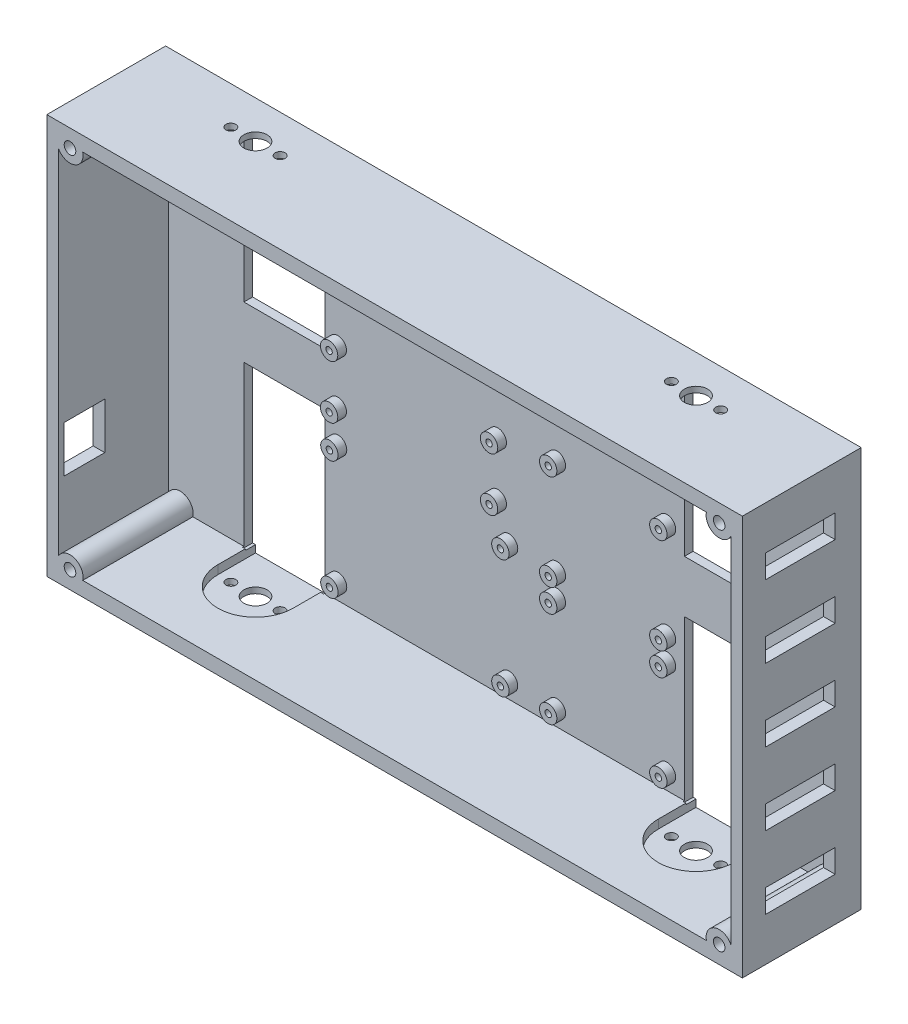
SolidWorks part; units mm, degrees
ref_plane "Front Plane" through (0, 0, 0) normal (0, 0, 1) x (1, 0, 0)
ref_plane "Top Plane" through (0, 0, 0) normal (0, 1, 0) x (1, 0, 0)
ref_plane "Right Plane" through (0, 0, 0) normal (1, 0, 0) x (0, 0, -1)
ref_plane "P_Front_57" through (0, 0, 57) normal (0, 0, 1) x (1, 0, 0)
sketch "Sketch1" plane through (0, 0, 57) normal (0, 0, 1) x (1, 0, 0)
  line L0 (-120, -69) -> (120, -69)
  line L1 (120, -69) -> (120, 69)
  line L2 (120, 69) -> (-120, 69)
  line L3 (-120, 69) -> (-120, -69)
extrude "Floor" add sketch "Sketch1" along normal blind 3
ref_plane "P_Front_60" through (0, 0, 60) normal (0, 0, 1) x (1, 0, 0)
sketch "Sketch2" plane through (0, 0, 60) normal (0, 0, 1) x (1, 0, 0)
  line L0 (-120, -69) -> (120, -69)
  line L1 (120, -69) -> (120, 69)
  line L2 (120, 69) -> (-120, 69)
  line L3 (-120, 69) -> (-120, -69)
  line L4 (-116, -64) -> (116, -64)
  line L5 (116, -64) -> (116, 64)
  line L6 (116, 64) -> (-116, 64)
  line L7 (-116, 64) -> (-116, -64)
extrude "Walls" add sketch "Sketch2" along normal blind 38
sketch "Sketch3" plane through (0, 0, 60) normal (0, 0, 1) x (1, 0, 0)
  circle A0 centre (-112, 63) radius 4.5
  circle A1 centre (-112, -63) radius 4.5
  circle A2 centre (112, 63) radius 4.5
  circle A3 centre (112, -63) radius 4.5
extrude "Insert_columns" add sketch "Sketch3" along normal blind 38
sketch "Sketch4" plane through (0, 0, 60) normal (0, 0, 1) x (1, 0, 0)
  circle A0 centre (1.5, -17.5) radius 3
  circle A1 centre (1.5, -58.5) radius 3
  circle A2 centre (-57.5, -17.5) radius 3
  circle A3 centre (-57.5, -58.5) radius 3
  circle A4 centre (56, -25.5) radius 3
  circle A5 centre (56, -58.5) radius 3
  circle A6 centre (18, -25.5) radius 3
  circle A7 centre (18, -58.5) radius 3
  circle A8 centre (56, 15.5) radius 3
  circle A9 centre (56, -17.5) radius 3
  circle A10 centre (18, 15.5) radius 3
  circle A11 centre (18, -17.5) radius 3
  circle A12 centre (-2.4, 12.2) radius 3
  circle A13 centre (-2.4, -6.2) radius 3
  circle A14 centre (-57.6, 12.2) radius 3
  circle A15 centre (-57.6, -6.2) radius 3
  circle A16 centre (-107, 47.5) radius 3
  circle A17 centre (-97, 47.5) radius 3
  circle A18 centre (-107, 32.5) radius 3
  circle A19 centre (-97, 32.5) radius 3
extrude "Board_standoffs" add sketch "Sketch4" along normal blind 3
ref_plane "P_Front_59" through (0, 0, 59) normal (0, 0, 1) x (1, 0, 0)
sketch "Sketch5" plane through (0, 0, 59) normal (0, 0, 1) x (1, 0, 0)
  circle A0 centre (1.5, -17.5) radius 1.1
  circle A1 centre (1.5, -58.5) radius 1.1
  circle A2 centre (-57.5, -17.5) radius 1.1
  circle A3 centre (-57.5, -58.5) radius 1.1
  circle A4 centre (56, -25.5) radius 1.1
  circle A5 centre (56, -58.5) radius 1.1
  circle A6 centre (18, -25.5) radius 1.1
  circle A7 centre (18, -58.5) radius 1.1
  circle A8 centre (56, 15.5) radius 1.1
  circle A9 centre (56, -17.5) radius 1.1
  circle A10 centre (18, 15.5) radius 1.1
  circle A11 centre (18, -17.5) radius 1.1
  circle A12 centre (-2.4, 12.2) radius 1.1
  circle A13 centre (-2.4, -6.2) radius 1.1
  circle A14 centre (-57.6, 12.2) radius 1.1
  circle A15 centre (-57.6, -6.2) radius 1.1
  circle A16 centre (-107, 47.5) radius 1.1
  circle A17 centre (-97, 47.5) radius 1.1
  circle A18 centre (-107, 32.5) radius 1.1
  circle A19 centre (-97, 32.5) radius 1.1
extrude "Standoff_pilots" cut sketch "Sketch5" along normal blind 5
ref_plane "P_Front_56" through (0, 0, 56) normal (0, 0, 1) x (1, 0, 0)
sketch "Sketch6" plane through (0, 0, 56) normal (0, 0, 1) x (1, 0, 0)
  line L0 (62, 9) -> (90, 9)
  line L1 (90, 9) -> (90, 64.5)
  line L2 (90, 64.5) -> (62, 64.5)
  line L3 (62, 64.5) -> (62, 9)
  line L4 (62, -64.5) -> (90, -64.5)
  line L5 (90, -64.5) -> (90, -9)
  line L6 (90, -9) -> (62, -9)
  line L7 (62, -9) -> (62, -64.5)
  line L8 (-90, 9) -> (-62, 9)
  line L9 (-62, 9) -> (-62, 64.5)
  line L10 (-62, 64.5) -> (-90, 64.5)
  line L11 (-90, 64.5) -> (-90, 9)
  line L12 (-90, -64.5) -> (-62, -64.5)
  line L13 (-62, -64.5) -> (-62, -9)
  line L14 (-62, -9) -> (-90, -9)
  line L15 (-90, -9) -> (-90, -64.5)
extrude "Motor_floor_windows" cut sketch "Sketch6" along normal blind 4.5
ref_plane "P_Top_64" through (0, 64, 0) normal (0, 1, 0) x (1, 0, 0)
sketch "Sketch7" plane through (0, 64, 0) normal (0, 1, 0) x (1, 0, 0)
  line L0 (89, -70) -> (89, -52)
  line L1 (89, -52) -> (63, -52)
  line L2 (63, -52) -> (63, -70)
  line L3 (-63, -70) -> (-63, -52)
  line L4 (-63, -52) -> (-89, -52)
  line L5 (-89, -52) -> (-89, -70)
  arc A0 (63, -70) -> (89, -70) centre (76, -70) ccw
  arc A1 (-89, -70) -> (-63, -70) centre (-76, -70) ccw
extrude "Motor_pocket_L" cut sketch "Sketch7" along normal blind 3
ref_plane "P_Top_m67" through (0, -67, 0) normal (0, 1, 0) x (1, 0, 0)
sketch "Sketch8" plane through (0, -67, 0) normal (0, 1, 0) x (1, 0, 0)
  line L0 (89, -70) -> (89, -52)
  line L1 (89, -52) -> (63, -52)
  line L2 (63, -52) -> (63, -70)
  line L3 (-63, -70) -> (-63, -52)
  line L4 (-63, -52) -> (-89, -52)
  line L5 (-89, -52) -> (-89, -70)
  arc A0 (63, -70) -> (89, -70) centre (76, -70) ccw
  arc A1 (-89, -70) -> (-63, -70) centre (-76, -70) ccw
extrude "Motor_pocket_R" cut sketch "Sketch8" along normal blind 3
sketch "Sketch9" plane through (0, 0, 0) normal (0, 1, 0) x (1, 0, 0)
  circle A0 centre (76, -70) radius 4
  circle A1 centre (67.5, -70) radius 1.7
  circle A2 centre (84.5, -70) radius 1.7
  circle A3 centre (-76, -70) radius 4
  circle A4 centre (-84.5, -70) radius 1.7
  circle A5 centre (-67.5, -70) radius 1.7
extrude "Motor_shaft_and_M3_holes" cut sketch "Sketch9" along normal through all and the other way through all
ref_plane "P_Front_98" through (0, 0, 98) normal (0, 0, 1) x (1, 0, 0)
sketch "Sketch10" plane through (0, 0, 98) normal (0, 0, 1) x (1, 0, 0)
  circle A0 centre (-112, 63) radius 2
  circle A1 centre (-112, -63) radius 2
  circle A2 centre (112, 63) radius 2
  circle A3 centre (112, -63) radius 2
extrude "M3_insert_bores" cut sketch "Sketch10" against normal blind 8
sketch "Sketch11" plane through (0, 0, 56) normal (0, 0, 1) x (1, 0, 0)
  circle A0 centre (61, 42) radius 1.7
  circle A1 centre (-61, 42) radius 1.7
extrude "Cradle_M3_holes" cut sketch "Sketch11" along normal blind 5
ref_plane "P_Right_m121" through (-121, 0, 0) normal (1, 0, 0) x (0, 0, -1)
sketch "Sketch12" plane through (-121, 0, 0) normal (1, 0, 0) x (0, 0, -1)
  line L0 (-96, -38) -> (-82, -38)
  line L1 (-82, -38) -> (-82, -22)
  line L2 (-82, -22) -> (-96, -22)
  line L3 (-96, -22) -> (-96, -38)
extrude "USB_grommet" cut sketch "Sketch12" along normal blind 6
ref_plane "P_Right_115" through (115, 0, 0) normal (1, 0, 0) x (0, 0, -1)
sketch "Sketch13" plane through (115, 0, 0) normal (1, 0, 0) x (0, 0, -1)
  line L0 (-90, -54) -> (-66, -54)
  line L1 (-66, -54) -> (-66, -46)
  line L2 (-66, -46) -> (-90, -46)
  line L3 (-90, -46) -> (-90, -54)
  line L4 (-90, -29) -> (-66, -29)
  line L5 (-66, -29) -> (-66, -21)
  line L6 (-66, -21) -> (-90, -21)
  line L7 (-90, -21) -> (-90, -29)
  line L8 (-90, -4) -> (-66, -4)
  line L9 (-66, -4) -> (-66, 4)
  line L10 (-66, 4) -> (-90, 4)
  line L11 (-90, 4) -> (-90, -4)
  line L12 (-90, 21) -> (-66, 21)
  line L13 (-66, 21) -> (-66, 29)
  line L14 (-66, 29) -> (-90, 29)
  line L15 (-90, 29) -> (-90, 21)
  line L16 (-90, 46) -> (-66, 46)
  line L17 (-66, 46) -> (-66, 54)
  line L18 (-66, 54) -> (-90, 54)
  line L19 (-90, 54) -> (-90, 46)
extrude "Vent_slots" cut sketch "Sketch13" along normal blind 6
